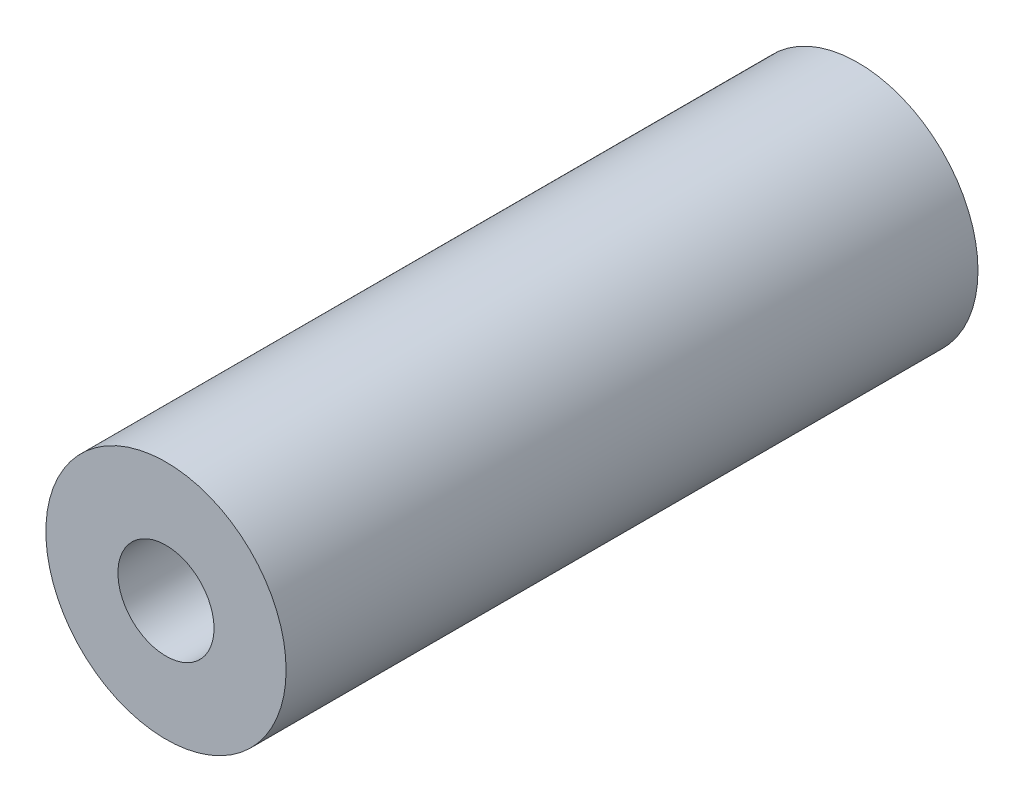
SolidWorks part; units mm, degrees
material "ABS"
ref_plane "Front Plane" through (0, 0, 0) normal (0, 0, 1) x (1, 0, 0)
ref_plane "Top Plane" through (0, 0, 0) normal (0, 1, 0) x (1, 0, 0)
ref_plane "Right Plane" through (0, 0, 0) normal (1, 0, 0) x (0, 0, -1)
sketch "Sketch1" plane through (0, 0, 0) normal (0, 0, 1) x (1, 0, 0)
  circle A0 centre (0, 0) radius 1.27
  circle A1 centre (0, 0) radius 3.175
  dimension "D1" = 2.54
  dimension "D2" = 6.35
extrude "Boss-Extrude2" add sketch "Sketch1" along normal blind 18.288 contours A1 | A0
